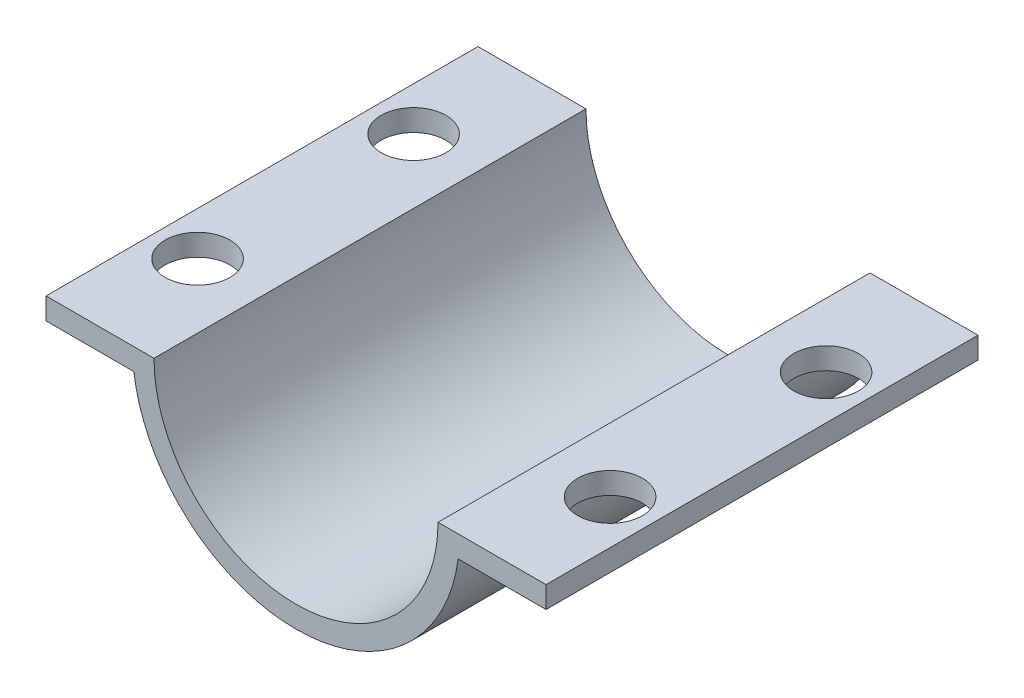
SolidWorks part; units mm, degrees
material "Gray Cast Iron"
ref_plane "Front" through (0, 0, 0) normal (0, 0, 1) x (1, 0, 0)
ref_plane "Top" through (0, 0, 0) normal (0, 1, 0) x (1, 0, 0)
ref_plane "Right" through (0, 0, 0) normal (1, 0, 0) x (0, 0, -1)
sketch "Sketch1" plane through (0, 0, 0) normal (0, 0, 1) x (1, 0, 0)
  line L0 (-16.7005, 0) -> (0, 0) construction
  line L1 (0, 0) -> (16.7005, 0) construction
  line L2 (-16.7005, 0) -> (-29.4005, 0)
  line L3 (16.7005, 0) -> (29.4005, 0)
  arc A0 (-16.7005, 0) -> (16.7005, 0) centre (0, 0) ccw
  dimension "D3" = 16.7005
  dimension "D1" = 12.7
  dimension "D2" = 12.7
extrude "Extrude-Thin1" add sketch "Sketch1" along normal mid plane 50.8 thin thin type one direction wall 2.54
sketch "Sketch2" plane through (0, -2.54, 0) normal (0, -1, 0) x (1, 0, 0)
  line L0 (19.0721, -25.4) -> (29.4005, -25.4) construction
  line L1 (19.0721, 25.4) -> (29.4005, 25.4) construction
  line L2 (-29.4005, 25.4) -> (-19.0721, 25.4) construction
  circle A0 centre (24.2363, -12.7) radius 3.81
  circle A1 centre (24.2363, 12.7) radius 3.81
  circle A2 centre (-24.2777, 12.7) radius 3.81
  circle A3 centre (-24.2777, -12.7) radius 3.81
  point P4 (-24.2363, 25.4)
  point P7 (24.2363, -25.4)
  point P8 (24.2363, 25.4)
  dimension "D1" = 7.62
  dimension "D2" = 7.62
  dimension "D3" = 12.7
  dimension "D4" = 12.7
  dimension "D5" = 2
extrude "Cut-Extrude1" cut sketch "Sketch2" against normal blind 8.128
